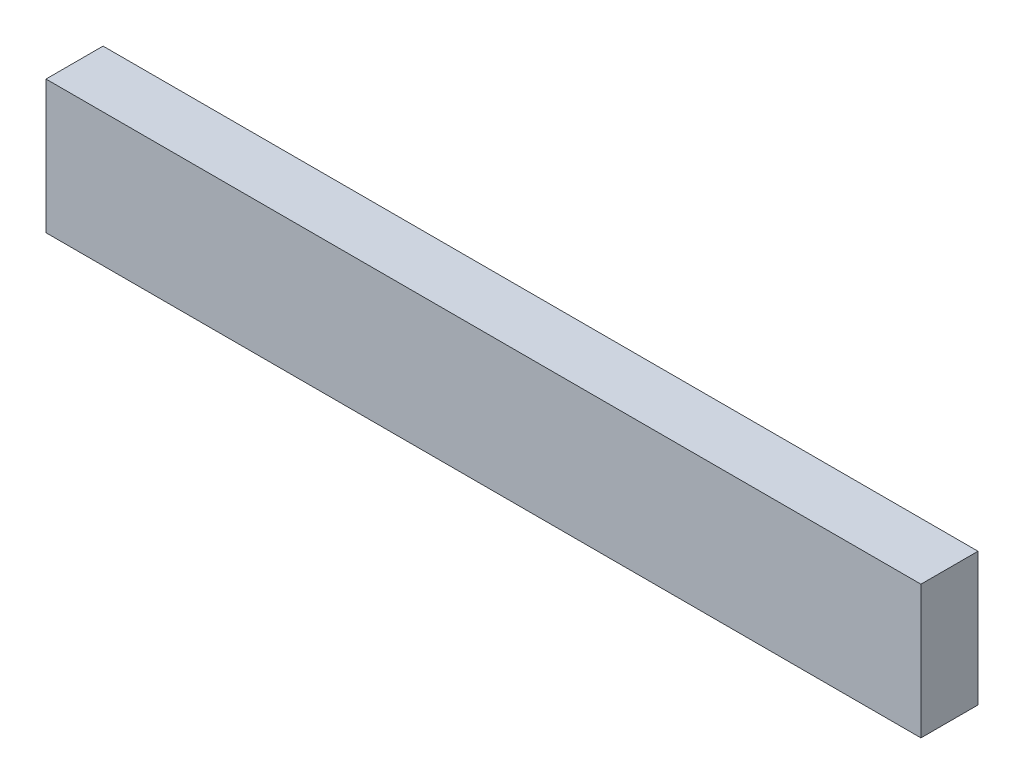
SolidWorks part; units mm, degrees
material "Pine"
ref_plane "Front Plane" through (0, 0, 0) normal (0, 0, 1) x (1, 0, 0)
ref_plane "Top Plane" through (0, 0, 0) normal (0, 1, 0) x (1, 0, 0)
ref_plane "Right Plane" through (0, 0, 0) normal (1, 0, 0) x (0, 0, -1)
sketch "Sketch1" plane through (0, 0, 0) normal (1, 0, 0) x (0, 0, -1)
  line L1 (-19.05, -44.45) -> (19.05, -44.45)
  line L2 (-19.05, -44.45) -> (-19.05, 44.45)
  line L3 (-19.05, 44.45) -> (19.05, 44.45)
  line L4 (19.05, -44.45) -> (19.05, 44.45)
  line L5 (-19.05, -44.45) -> (19.05, 44.45) construction
  line L6 (-19.05, 44.45) -> (19.05, -44.45) construction
  point P0 (0, 0)
  dimension "D1" = 88.9
  dimension "D2" = 38.1
extrude "Boss-Extrude1" add sketch "Sketch1" along normal blind 584.2
